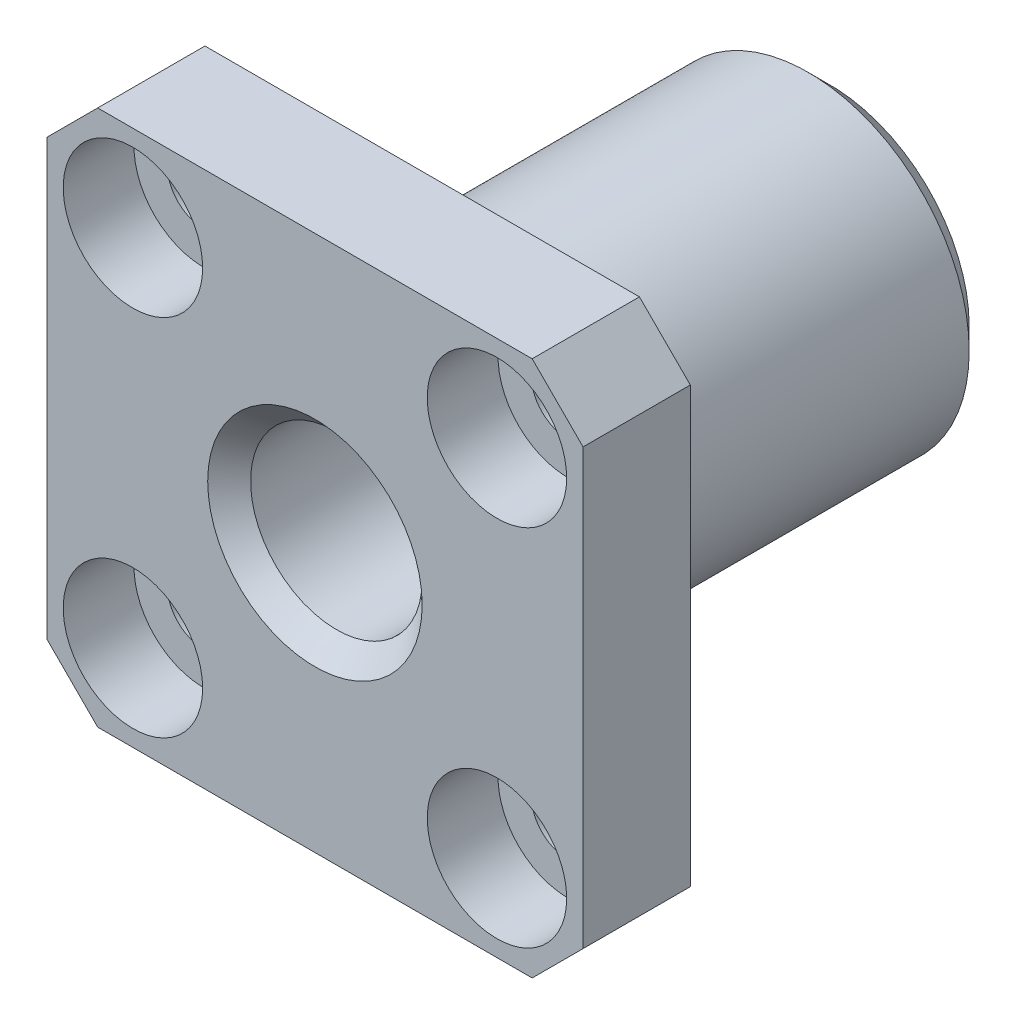
SolidWorks part; units mm, degrees
ref_plane "Front Plane" through (0, 0, 0) normal (0, 0, 1) x (1, 0, 0)
ref_plane "Top Plane" through (0, 0, 0) normal (0, 1, 0) x (1, 0, 0)
ref_plane "Right Plane" through (0, 0, 0) normal (1, 0, 0) x (0, 0, -1)
sketch "Sketch1" plane through (0, 0, 0) normal (0, 0, 1) x (1, 0, 0)
  circle A0 centre (0, 0) radius 7.5
  dimension "D1" = 15
extrude "Boss-Extrude1" add sketch "Sketch1" along normal blind 24
sketch "Sketch2" plane through (0, 0, 24) normal (0, 0, 1) x (1, 0, 0)
  line L1 (-12.5, -12.5) -> (12.5, -12.5)
  line L2 (-12.5, -12.5) -> (-12.5, 12.5)
  line L3 (-12.5, 12.5) -> (12.5, 12.5)
  line L4 (12.5, -12.5) -> (12.5, 12.5)
  line L5 (-12.5, -12.5) -> (12.5, 12.5) construction
  line L6 (-12.5, 12.5) -> (12.5, -12.5) construction
  point P0 (0, 0)
  dimension "D1" = 25
extrude "Boss-Extrude2" add sketch "Sketch2" against normal blind 5
sketch "Sketch4" plane through (0, 0, 24) normal (0, 0, 1) x (1, 0, 0)
  line L0 (0, 12.5) -> (0, -12.5) construction
  line L1 (12.5, 12.5) -> (-12.5, 12.5) construction
  line L2 (-12.5, -12.5) -> (12.5, -12.5) construction
  line L3 (-12.5, 12.5) -> (-12.5, 10.1274)
  line L4 (-12.5, 12.5) -> (-12.5, -12.5) construction
  line L5 (-12.5, 10.1274) -> (-10.1274, 12.5)
  line L6 (-10.1274, 12.5) -> (-12.5, 12.5)
  line L7 (10.1274, 12.5) -> (12.5, 12.5)
  line L8 (12.5, 10.1274) -> (10.1274, 12.5)
  line L9 (12.5, 12.5) -> (12.5, 10.1274)
  line L10 (-12.5, 0) -> (12.5, 0) construction
  line L11 (12.5, -12.5) -> (12.5, 12.5) construction
  line L12 (12.5, -12.5) -> (12.5, -10.1274)
  line L13 (12.5, -10.1274) -> (10.1274, -12.5)
  line L14 (10.1274, -12.5) -> (12.5, -12.5)
  line L15 (-10.1274, -12.5) -> (-12.5, -12.5)
  line L16 (-12.5, -10.1274) -> (-10.1274, -12.5)
  line L17 (-12.5, -12.5) -> (-12.5, -10.1274)
  dimension "D1" = 32
extrude "Cut-Extrude1" cut sketch "Sketch4" against normal through all
sketch "Sketch5" plane through (0, 0, 24) normal (0, 0, 1) x (1, 0, 0)
  line L0 (0, 0) -> (-11.3137, 11.3137) construction
  line L1 (-12.5, 10.1274) -> (-10.1274, 12.5) construction
  circle A0 centre (0, 0) radius 12 construction
  point P6 (-8.4853, 8.4853)
  point P10 (8.4853, 8.4853)
  point P11 (8.4853, -8.4853)
  point P12 (-8.4853, -8.4853)
  point P13 (0, 0)
  dimension "D1" = 24
  dimension "D2" = 4
hole_wizard "CBORE for M3 Hex Socket Head Cap Screw1" positions "Sketch6" profile "Sketch7" counterbore size "M3" standard "ISO"
sketch "Sketch6" plane through (0, 0, 24) normal (0, 0, 1) x (1, 0, 0)
  point P0 (-8.4853, 8.4853)
  point P3 (8.4853, 8.4853)
  point P6 (8.4853, -8.4853)
  point P9 (-8.4853, -8.4853)
sketch "Sketch7" plane through (-8.4853, 8.4853, 24) normal (1, 0, 0) x (0, -1, 0)
  line L0 (0, 0) -> (0, 23.0215)
  line L1 (0, 23.0215) -> (1.7, 22)
  line L2 (1.7, 22) -> (1.7, 3.3)
  line L3 (1.7, 3.3) -> (3.25, 3.3)
  line L4 (3.25, 3.3) -> (3.25, 0)
  line L5 (3.25, 0) -> (0, 0)
  line L10 (0, 23.0215) -> (-1.7, 22) construction
  line L11 (0, -6.35) -> (0, 107.95) construction
  dimension "Hole Dia." = 3.4
  dimension "Hole Depth" = 22
  dimension "C'Bore Dia." = 6.5
  dimension "C'Bore Depth" = 3.3
  dimension "Drill Angle" = 118
sketch "Sketch8" plane through (0, 0, 24) normal (0, 0, 1) x (1, 0, 0)
  circle A0 centre (0, 0) radius 4
  dimension "D1" = 8
extrude "Cut-Extrude2" cut sketch "Sketch8" against normal through all
chamfer "Chamfer1" distance 1 angle 45 2 edges at (7.5, 0, 0) (4, 0, 24)
